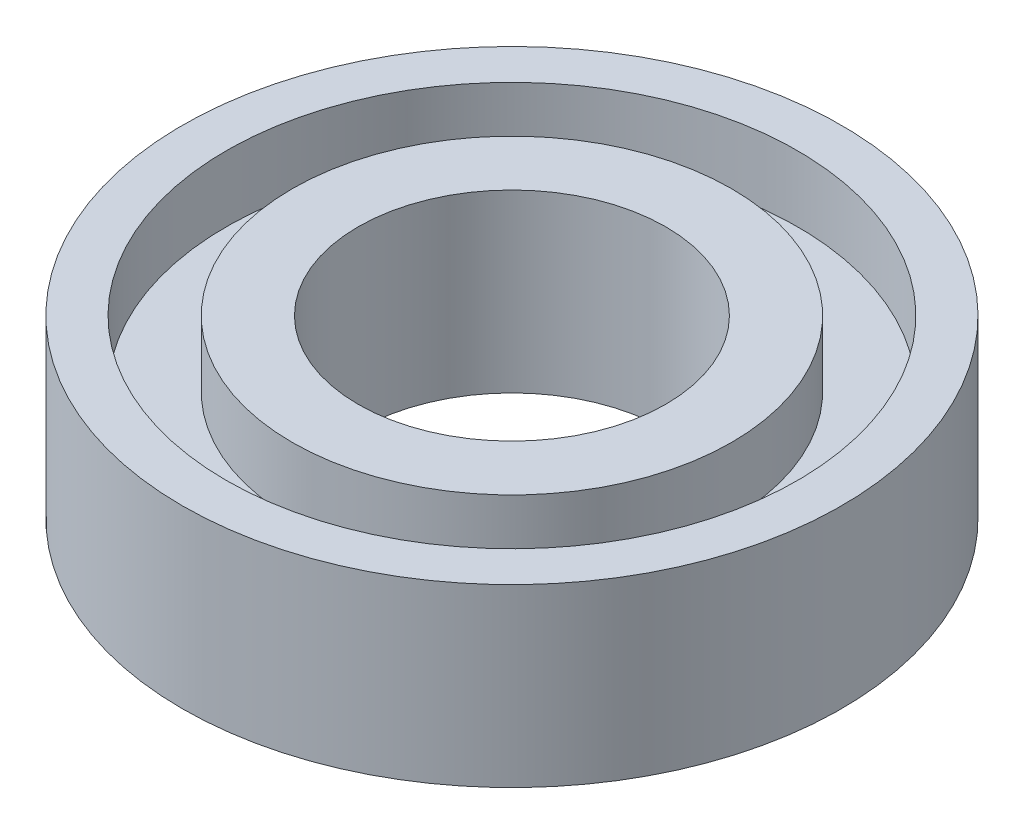
SolidWorks part; units mm, degrees
ref_plane "Front Plane" through (0, 0, 0) normal (0, 0, 1) x (1, 0, 0)
ref_plane "Top Plane" through (0, 0, 0) normal (0, 1, 0) x (1, 0, 0)
ref_plane "Right Plane" through (0, 0, 0) normal (1, 0, 0) x (0, 0, -1)
sketch "Sketch2" plane through (0, 0, 0) normal (0, 1, 0) x (1, 0, 0)
  circle A0 centre (0, 0) radius 7
  circle A1 centre (0, 0) radius 15
  dimension "D1" = 14
  dimension "D2" = 30
extrude "Boss-Extrude1" add sketch "Sketch2" along normal blind 8
sketch "Sketch3" plane through (0, 8, 0) normal (0, 1, 0) x (1, 0, 0)
  circle A0 centre (0, 0) radius 10
  circle A1 centre (0, 0) radius 13
  dimension "D1" = 20
  dimension "D2" = 26
extrude "Cut-Extrude1" cut sketch "Sketch3" against normal blind 3
